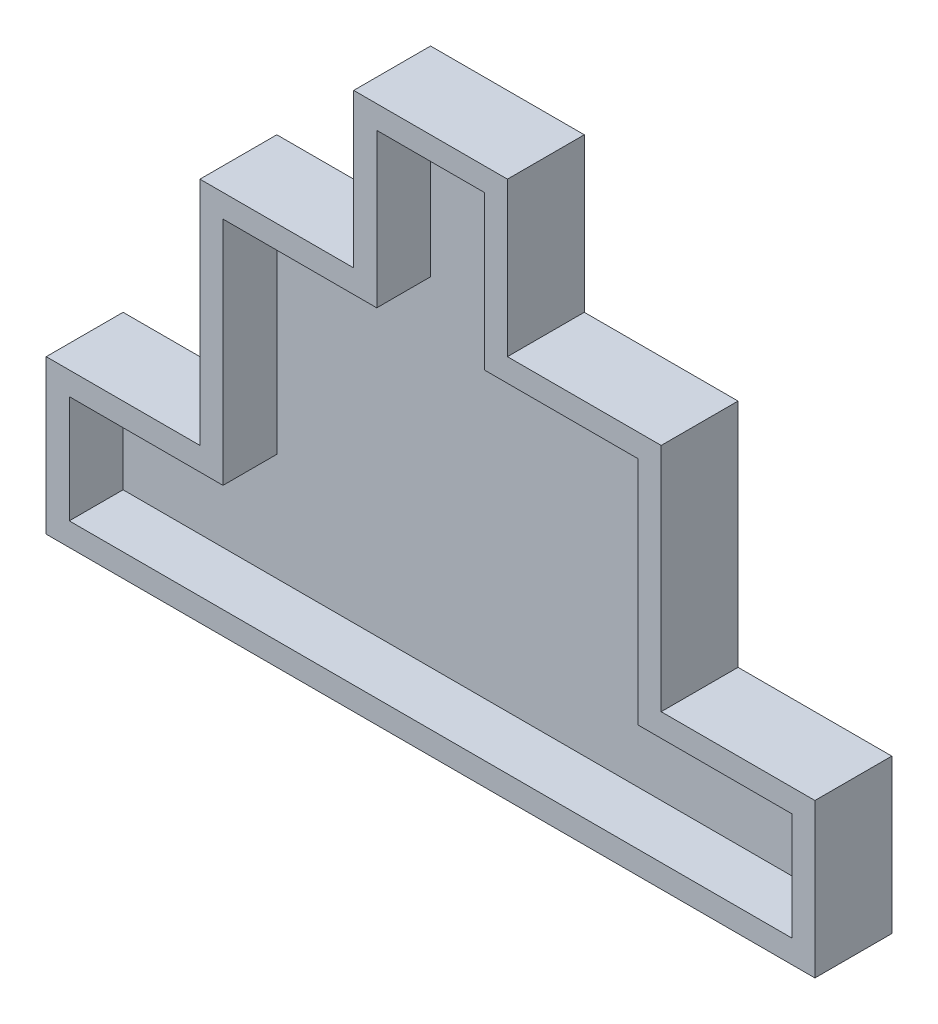
SolidWorks part; units mm, degrees
ref_plane "Ön Düzlem" through (0, 0, 0) normal (0, 0, 1) x (1, 0, 0)
ref_plane "Üst Düzlem" through (0, 0, 0) normal (0, 1, 0) x (1, 0, 0)
ref_plane "Sağ Düzlem" through (0, 0, 0) normal (1, 0, 0) x (0, 0, -1)
sketch "Çizim2" plane through (0, 0, 0) normal (0, 0, 1) x (1, 0, 0)
  line L0 (-75, -52.5) -> (-75, -22.5)
  line L1 (-75, -22.5) -> (-45, -22.5)
  line L2 (-45, -22.5) -> (-45, 22.5)
  line L3 (-45, 22.5) -> (-15, 22.5)
  line L4 (-15, 22.5) -> (-15, 52.5)
  line L5 (-15, 52.5) -> (15, 52.5)
  line L6 (0, 52.5) -> (0, -52.5) construction
  line L7 (15, 22.5) -> (15, 52.5)
  line L8 (45, 22.5) -> (15, 22.5)
  line L9 (45, -22.5) -> (45, 22.5)
  line L10 (75, -22.5) -> (45, -22.5)
  line L11 (75, -52.5) -> (75, -22.5)
  line L12 (-75, -52.5) -> (75, -52.5)
  dimension "D1" = 30
  dimension "D2" = 45
  dimension "D3" = 30
  dimension "D4" = 30
  dimension "D5" = 30
  dimension "D6" = 15
extrude "Yükseklik-Ekstrüzyon3" add sketch "Çizim2" along normal blind 4.5 contours L3 L4 L5 L7 L8 L9 L10 L11 L12 L0 L1 L2
sketch "Çizim4" plane through (0, 0, 4.5) normal (0, 0, 1) x (1, 0, 0)
  line L24 (-40.5, 18) -> (-40.5, -27)
  line L25 (-40.5, -27) -> (-70.5, -27)
  line L26 (-70.5, -27) -> (-70.5, -48)
  line L27 (-70.5, -48) -> (70.5, -48)
  line L28 (70.5, -48) -> (70.5, -27)
  line L29 (70.5, -27) -> (40.5, -27)
  line L30 (40.5, -27) -> (40.5, 18)
  line L31 (40.5, 18) -> (10.5, 18)
  line L32 (10.5, 18) -> (10.5, 48)
  line L33 (10.5, 48) -> (-10.5, 48)
  line L34 (-10.5, 48) -> (-10.5, 18)
  line L35 (-10.5, 18) -> (-40.5, 18)
  line L36 (-40.5, 18) -> (-40.5, -27)
  line L37 (-40.5, -27) -> (-70.5, -27)
  line L38 (-70.5, -27) -> (-70.5, -48)
  line L39 (-70.5, -48) -> (70.5, -48)
  line L40 (70.5, -48) -> (70.5, -27)
  line L41 (70.5, -27) -> (40.5, -27)
  line L42 (40.5, -27) -> (40.5, 18)
  line L43 (40.5, 18) -> (10.5, 18)
  line L44 (10.5, 18) -> (10.5, 48)
  line L45 (10.5, 48) -> (-10.5, 48)
  line L46 (-10.5, 48) -> (-10.5, 18)
  line L47 (-10.5, 18) -> (-40.5, 18)
  line M13 (-45, 22.5) -> (-45, -22.5)
  line M14 (-45, -22.5) -> (-75, -22.5)
  line M15 (-75, -22.5) -> (-75, -52.5)
  line M16 (-75, -52.5) -> (75, -52.5)
  line M17 (75, -52.5) -> (75, -22.5)
  line M18 (75, -22.5) -> (45, -22.5)
  line M19 (45, -22.5) -> (45, 22.5)
  line M20 (45, 22.5) -> (15, 22.5)
  line M21 (15, 22.5) -> (15, 52.5)
  line M22 (15, 52.5) -> (-15, 52.5)
  line M23 (-15, 52.5) -> (-15, 22.5)
  line M24 (-15, 22.5) -> (-45, 22.5)
  dimension "D1" = 4.5
extrude "Yükseklik-Ekstrüzyon4" add sketch "Çizim4" along normal blind 10.5 contours L47 L46 L45 L44 L43 L42 L41 L40 L39 L38 L37 L36 M24 M13 M14 M15 M16 M17 M18 M19 M20 M21 M22 M23
